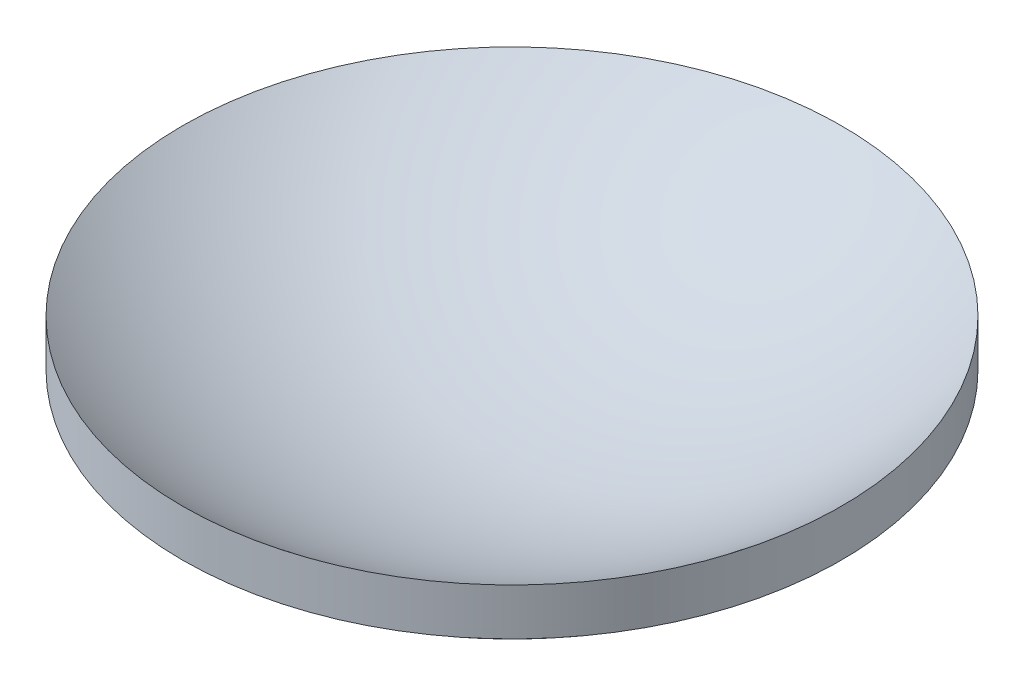
SolidWorks part; units mm, degrees
ref_plane "Front Plane" through (0, 0, 0) normal (0, 0, 1) x (1, 0, 0)
ref_plane "Top Plane" through (0, 0, 0) normal (0, 1, 0) x (1, 0, 0)
ref_plane "Right Plane" through (0, 0, 0) normal (1, 0, 0) x (0, 0, -1)
sketch "Sketch1" plane through (0, 0, 0) normal (0, 0, 1) x (1, 0, 0)
  line L0 (-4500, -6000) -> (-4500, -5361.9026)
  line L1 (0, -7500) -> (0, -7000)
  line L2 (0, 0) -> (0, -7828.3404) construction
  arc A0 (0, -7500) -> (-4500, -6000) centre (0, 0) cw
  arc A1 (0, -7000) -> (-4500, -5361.9026) centre (0, 0) cw
  dimension "D1" = 4500
  dimension "D2" = 1500
  dimension "D4" = 500
revolve "Revolve1" add sketch "Sketch1" angle 360 about L2
